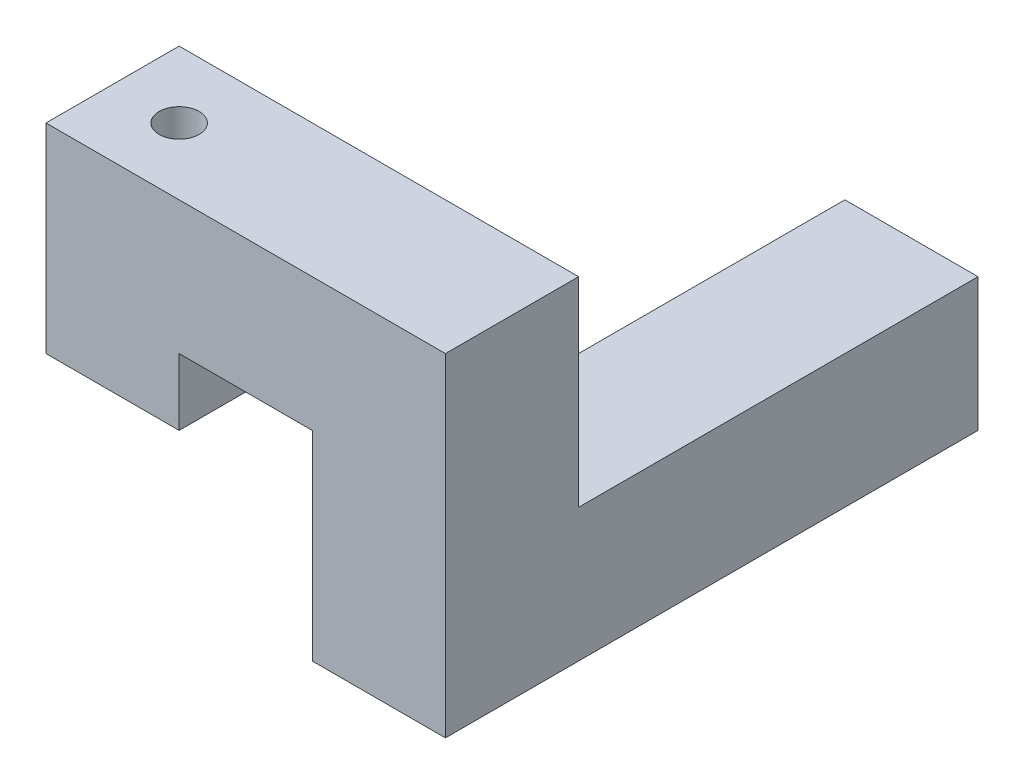
SolidWorks part; units mm, degrees
ref_plane "前视基准面" through (0, 0, 0) normal (0, 0, 1) x (1, 0, 0)
ref_plane "上视基准面" through (0, 0, 0) normal (0, 1, 0) x (1, 0, 0)
ref_plane "右视基准面" through (0, 0, 0) normal (1, 0, 0) x (0, 0, -1)
other "Configuration Table"
sketch "草图1" plane through (0, 0, 0) normal (0, 1, 0) x (1, 0, 0)
  line L1 (-10, 10) -> (10, 10)
  line L2 (-10, 10) -> (-10, -10)
  line L3 (-10, -10) -> (10, -10)
  line L4 (10, 10) -> (10, -10)
  line L5 (-10, 10) -> (10, -10) construction
  line L6 (-10, -10) -> (10, 10) construction
  point P0 (0, 0)
  dimension "D1" = 20
  dimension "D2" = 20
extrude "凸台-拉伸1" add sketch "草图1" along normal blind 30
sketch "草图2" plane through (10, 0, 0) normal (1, 0, 0) x (0, 0, -1)
  line L0 (10, 30) -> (10, 0) construction
  line L1 (-10, 30) -> (10, 30)
  line L2 (-10, 30) -> (-10, 10)
  line L3 (-10, 10) -> (10, 10)
  line L4 (10, 30) -> (10, 10)
  dimension "D1" = 20
  dimension "D2" = 20
extrude "凸台-拉伸2" add sketch "草图2" along normal blind 40 contours L2 L1 L4 L3
sketch "草图6" plane through (0, 10, 0) normal (0, -1, 0) x (1, 0, 0)
  line L1 (50, -10) -> (10, -10) construction
  line L2 (50, 10) -> (30, 10)
  line L3 (50, 10) -> (50, -10)
  line L4 (50, -10) -> (30, -10)
  line L5 (30, 10) -> (30, -10)
extrude "凸台-拉伸3" add sketch "草图6" along normal blind 30 contours L3 L2 L5 L4
sketch "草图7" plane through (0, 0, -10) normal (0, 0, -1) x (-1, 0, 0)
  line L0 (-50, 30) -> (-50, -20) construction
  line L1 (-30, -20) -> (-50, -20)
  line L2 (-30, -20) -> (-30, 0)
  line L3 (-30, 0) -> (-50, 0)
  line L4 (-50, -20) -> (-50, 0)
extrude "凸台-拉伸4" add sketch "草图7" along normal blind 60
sketch "草图8" plane through (0, 0, 0) normal (0, -1, 0) x (-1, 0, 0)
  circle A0 centre (0, 0) radius 3
  dimension "D1" = 6
extrude "切除-拉伸1" cut sketch "草图8" against normal blind 60
sketch3d "3D草图4" plane through (0, 0, 0) normal (0, 0, 1) x (1, 0, 0)
